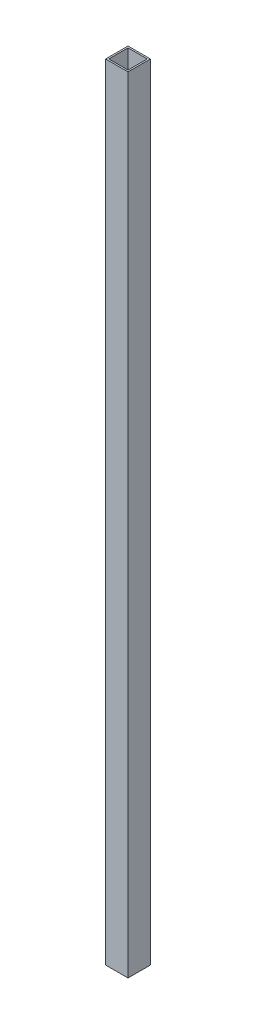
SolidWorks part; units mm, degrees
material "6061 Alloy"
ref_plane "Front Plane" through (0, 0, 0) normal (0, 0, 1) x (1, 0, 0)
ref_plane "Top Plane" through (0, 0, 0) normal (0, 1, 0) x (1, 0, 0)
ref_plane "Right Plane" through (0, 0, 0) normal (1, 0, 0) x (0, 0, -1)
sketch "Sketch1" plane through (0, 0, 0) normal (0, 1, 0) x (1, 0, 0)
  line L1 (-8.5, 8.5) -> (8.5, 8.5)
  line L2 (-8.5, 8.5) -> (-8.5, -8.5)
  line L3 (-8.5, -8.5) -> (8.5, -8.5)
  line L4 (8.5, 8.5) -> (8.5, -8.5)
  line L5 (-8.5, 8.5) -> (8.5, -8.5) construction
  line L6 (-8.5, -8.5) -> (8.5, 8.5) construction
  line L7 (-7.3, 7.3) -> (7.3, 7.3)
  line L8 (-7.3, 7.3) -> (-7.3, -7.3)
  line L9 (-7.3, -7.3) -> (7.3, -7.3)
  line L10 (7.3, 7.3) -> (7.3, -7.3)
  line L11 (-7.3, 7.3) -> (7.3, -7.3) construction
  line L12 (-7.3, -7.3) -> (7.3, 7.3) construction
  point P0 (0, 0)
  point P6 (0, 0)
  dimension "D1" = 14.6
  dimension "D2" = 17
extrude "Boss-Extrude1" add sketch "Sketch1" along normal blind 595 contours L1 L4 L3 L2 | L9 L10 L7 L8
